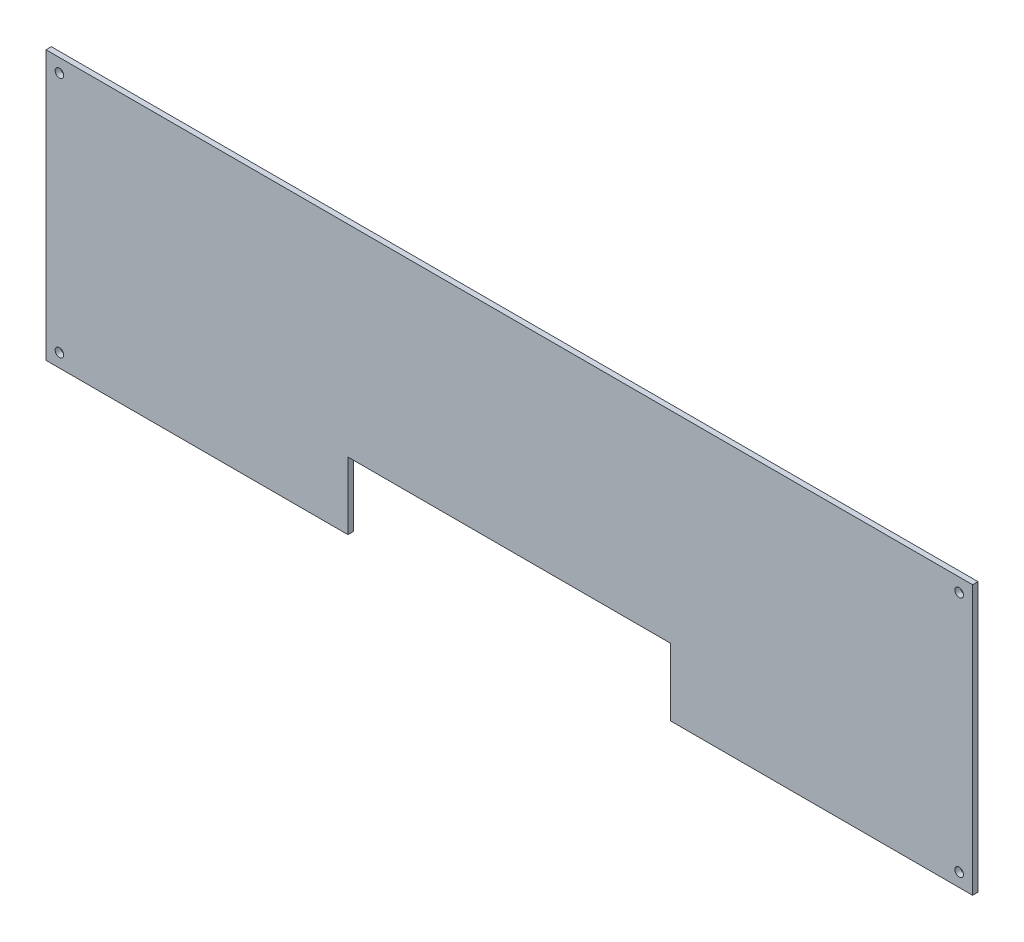
SolidWorks part; units mm, degrees
ref_plane "前视基准面" through (0, 0, 0) normal (0, 0, 1) x (1, 0, 0)
ref_plane "上视基准面" through (0, 0, 0) normal (0, 1, 0) x (1, 0, 0)
ref_plane "右视基准面" through (0, 0, 0) normal (1, 0, 0) x (0, 0, -1)
other "Configuration Table"
sketch "草图1" plane through (0, 0, 0) normal (0, 0, 1) x (1, 0, 0)
  line L1 (-172.25, 50) -> (172.25, 50)
  line L2 (-172.25, 50) -> (-172.25, -50)
  line L3 (-172.25, -50) -> (172.25, -50)
  line L4 (172.25, 50) -> (172.25, -50)
  line L5 (-172.25, 50) -> (172.25, -50) construction
  line L6 (-172.25, -50) -> (172.25, 50) construction
  point P0 (0, 0)
  dimension "D1" = 344.5
  dimension "D2" = 100
extrude "凸台-拉伸1" add sketch "草图1" along normal blind 2
sketch "草图2" plane through (0, 0, 2) normal (0, 0, 1) x (1, 0, 0)
  line L0 (-172.25, 50) -> (-172.25, -50) construction
  line L1 (172.25, 50) -> (-172.25, 50) construction
  line L3 (-172.25, -50) -> (172.25, -50) construction
  line L4 (172.25, -50) -> (172.25, 50) construction
  circle A0 centre (167.25, -45) radius 1.6
  circle A1 centre (167.25, 45) radius 1.6
  circle A2 centre (-167.25, -45) radius 1.6
  circle A3 centre (-167.25, 45) radius 1.6
  dimension "D1" = 3.2
  dimension "D7" = 3.2
  dimension "D8" = 3.2
  dimension "D9" = 3.2
  dimension "D2" = 5
  dimension "D3" = 5
  dimension "D4" = 90
  dimension "D5" = 334.5
  dimension "D6" = 90
  dimension "D10" = 5
  dimension "D11" = 5
  dimension "D12" = 5
extrude "切除-拉伸1" cut sketch "草图2" against normal blind 2
sketch "草图3" plane through (0, 0, 2) normal (0, 0, 1) x (1, 0, 0)
  line L0 (-172.25, -50) -> (172.25, -50) construction
  line L1 (-60, -25) -> (60, -25)
  line L2 (-60, -25) -> (-60, -50)
  line L3 (-60, -50) -> (60, -50)
  line L4 (60, -25) -> (60, -50)
  line L5 (-60, -25) -> (60, -50) construction
  line L6 (-60, -50) -> (60, -25) construction
  point P0 (0, -37.5)
  dimension "D1" = 25
  dimension "D2" = 120
extrude "切除-拉伸2" cut sketch "草图3" against normal blind 10
